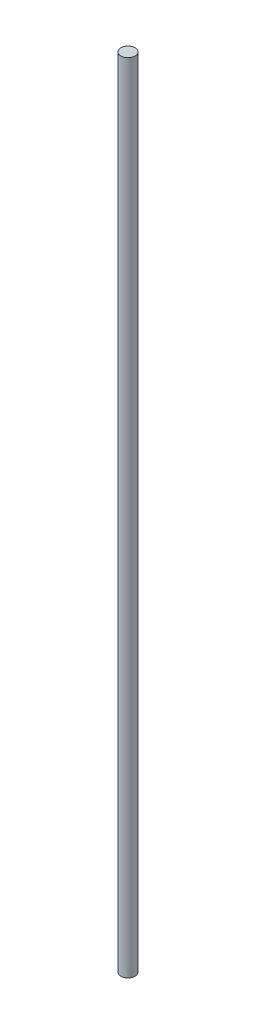
SolidWorks part; units mm, degrees
ref_plane "Front Plane" through (0, 0, 0) normal (0, 0, 1) x (1, 0, 0)
ref_plane "Top Plane" through (0, 0, 0) normal (0, 1, 0) x (1, 0, 0)
ref_plane "Right Plane" through (0, 0, 0) normal (1, 0, 0) x (0, 0, -1)
sketch "Sketch2" plane through (0, 0, 0) normal (0, 1, 0) x (1, 0, 0)
  circle A0 centre (0, 0) radius 1.5
  dimension "D1" = 3
extrude "Boss-Extrude1" add sketch "Sketch2" along normal blind 167.2
